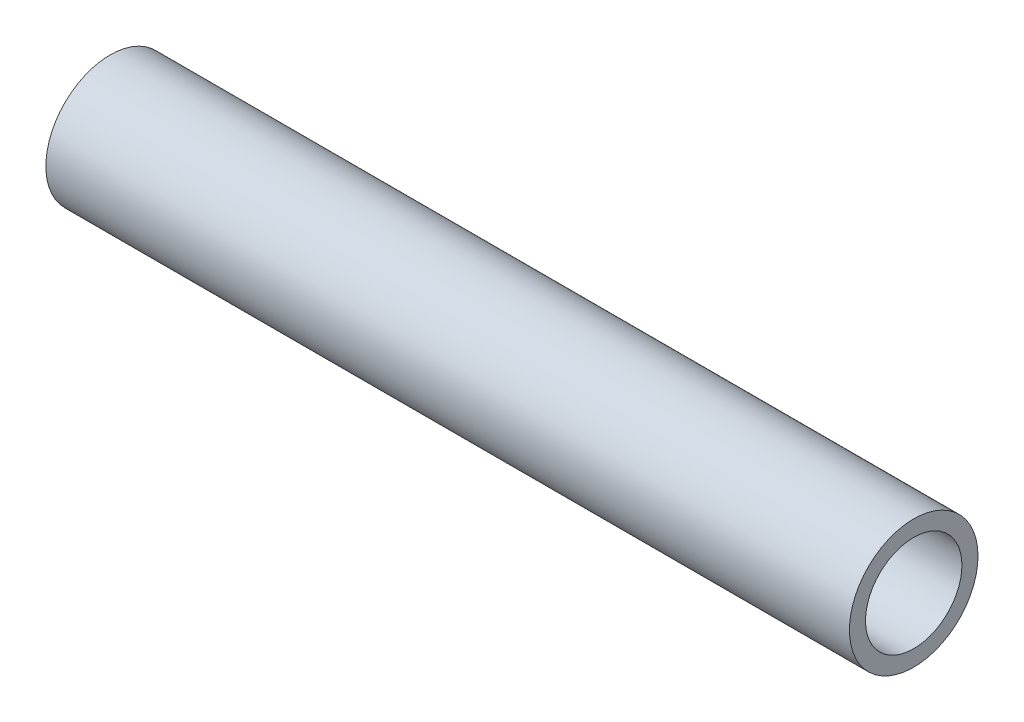
SolidWorks part; units mm, degrees
ref_plane "Front Plane" through (0, 0, 0) normal (0, 0, 1) x (1, 0, 0)
ref_plane "Top Plane" through (0, 0, 0) normal (0, 1, 0) x (1, 0, 0)
ref_plane "Right Plane" through (0, 0, 0) normal (1, 0, 0) x (0, 0, -1)
sketch "Sketch1" plane through (0, 0, 0) normal (1, 0, 0) x (0, 0, -1)
  circle A0 centre (0, 0) radius 4
  dimension "D1" = 8
extrude "Boss-Extrude1" add sketch "Sketch1" along normal blind 50
sketch "Sketch2" plane through (50, 0, 0) normal (1, 0, 0) x (0, 0, -1)
  circle A0 centre (0, 0) radius 3
  circle A1 centre (0, 0) radius 4 construction
  dimension "D1" = 1
extrude "Cut-Extrude1" cut sketch "Sketch2" against normal through all both and the other way through all
